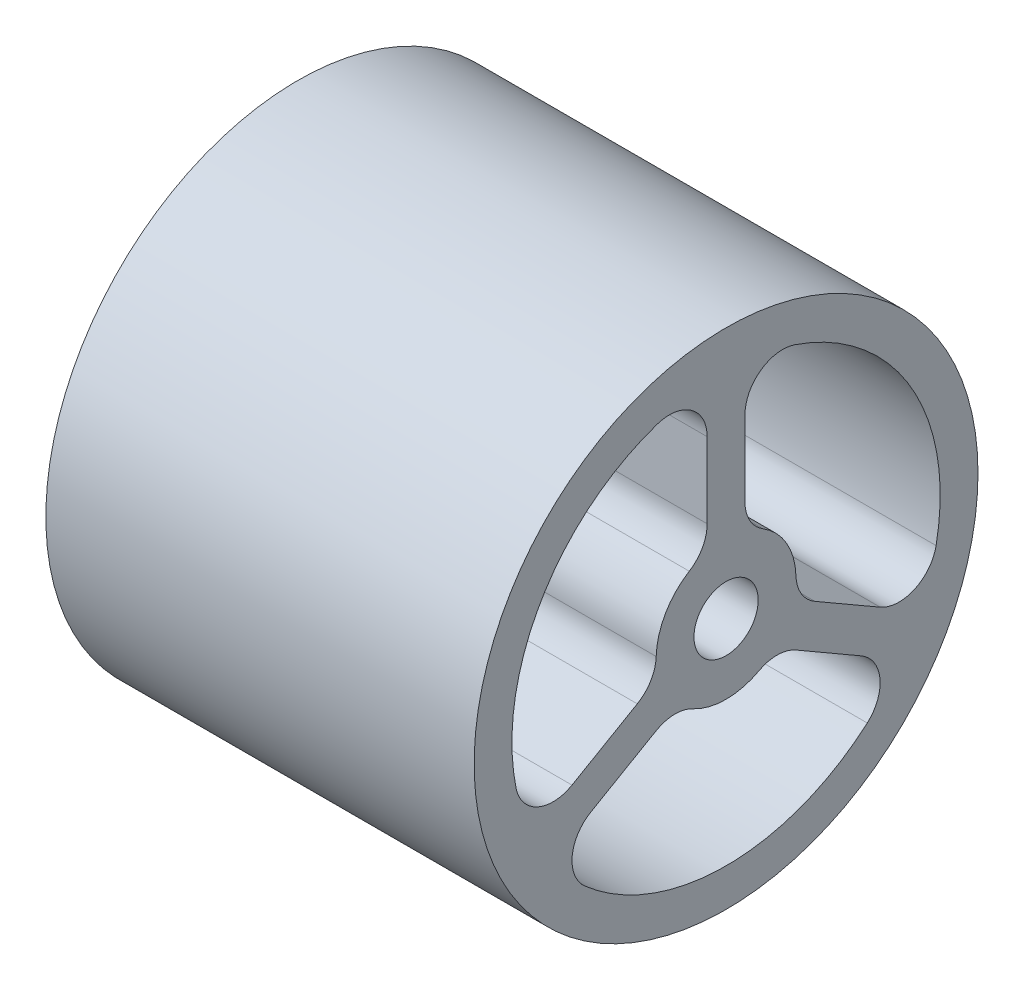
SolidWorks part; units mm, degrees
material "Delrin 2700 NC010, Low Viscosity Acetal Copolymer (SS)"
ref_plane "Front Plane" through (0, 0, 0) normal (0, 0, 1) x (1, 0, 0)
ref_plane "Top Plane" through (0, 0, 0) normal (0, 1, 0) x (1, 0, 0)
ref_plane "Right Plane" through (0, 0, 0) normal (1, 0, 0) x (0, 0, -1)
sketch "Sketch1" plane through (0, 0, 0) normal (1, 0, 0) x (0, 0, -1)
  line L1 (0, 5.55) -> (0, 17) construction
  line L2 (-1.5, 5.55) -> (-1.5, 17)
  line L3 (1.5, 5.55) -> (1.5, 17)
  line L4 (4.8064, -2.775) -> (14.7224, -8.5) construction
  line L5 (5.5564, -1.476) -> (15.4724, -7.201)
  line L6 (4.0564, -4.074) -> (13.9724, -9.799)
  line L7 (-4.8064, -2.775) -> (-14.7224, -8.5) construction
  line L8 (-4.0564, -4.074) -> (-13.9724, -9.799)
  line L9 (-5.5564, -1.476) -> (-15.4724, -7.201)
  line L10 (0, 0) -> (0, 5.55) construction
  circle A0 centre (0, 0) radius 20
  circle A1 centre (0, 0) radius 2.55
  circle A2 centre (0, 0) radius 17
  circle A3 centre (0, 0) radius 5.55
  arc A4 (-1.5, 5.55) -> (1.5, 5.55) centre (0, 5.55) ccw
  arc A5 (1.5, 17) -> (-1.5, 17) centre (0, 17) ccw
  arc A6 (5.5564, -1.476) -> (4.0564, -4.074) centre (4.8064, -2.775) ccw
  arc A7 (13.9724, -9.799) -> (15.4724, -7.201) centre (14.7224, -8.5) ccw
  arc A8 (-4.0564, -4.074) -> (-5.5564, -1.476) centre (-4.8064, -2.775) ccw
  arc A9 (-15.4724, -7.201) -> (-13.9724, -9.799) centre (-14.7224, -8.5) ccw
  point P9 (0, 11.275)
  point P18 (9.7644, -5.6375)
  point P25 (-9.7644, -5.6375)
  dimension "D1" = 40
  dimension "D2" = 5.1
  dimension "D3" = 3
  dimension "D4" = 3
  dimension "D5" = 3
  dimension "D7" = 5.55
  dimension "D6" = 3
extrude "Boss-Extrude1" add sketch "Sketch1" along normal blind 34 contours A0 A9 L9 A2 L2 A5 L3 L5 A7 L6 L8 | A8 A3 A6 A4 A1 | A3 A8 | L9 A9 L8 A2 | A3 A6 | A3 A4 | L6 A7 L5 A2 | L5 A6 A3 L6 A2 | A3 A8 L9 A2 L8 | L2 A4 A3 L3 A2 | L3 A5 L2 A2
fillet "Fillet1" radius 3 12 edges at (17, 16.9337, -1.5) (17, 5.3473, -1.4862) (17, 5.3473, 1.4862) (17, -1.3865, -5.374) (17, -3.9608, -3.8878) (17, -7.1678, -15.415) (17, -3.9608, 3.8878) (17, -1.3865, 5.374) (17, -9.7659, 13.915) (17, -9.7659, -13.915) (17, 16.9337, 1.5) (17, -7.1678, 15.415)
